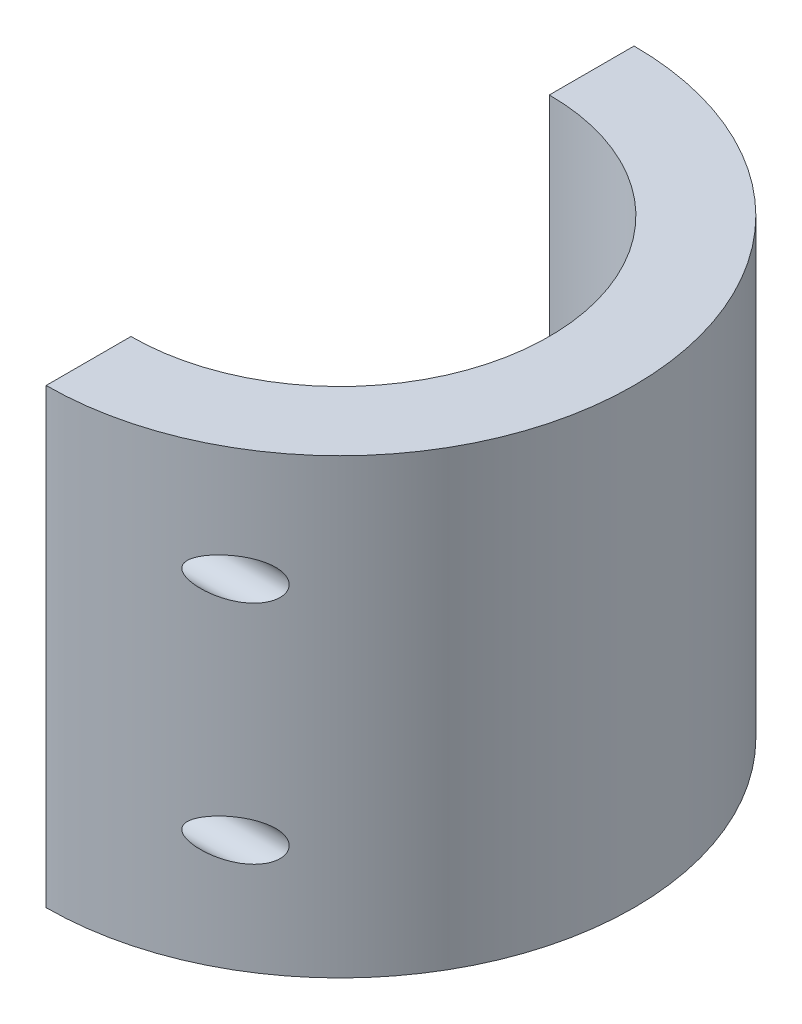
SolidWorks part; units mm, degrees
ref_plane "Front Plane" through (0, 0, 0) normal (0, 0, 1) x (1, 0, 0)
ref_plane "Top Plane" through (0, 0, 0) normal (0, 1, 0) x (1, 0, 0)
ref_plane "Right Plane" through (0, 0, 0) normal (1, 0, 0) x (0, 0, -1)
sketch "Sketch1" plane through (0, 0, 0) normal (0, 1, 0) x (1, 0, 0)
  line L0 (0, 13.208) -> (0, 9.398)
  line L1 (0, -9.398) -> (0, -13.208)
  arc A2 (0, -9.398) -> (0, 9.398) centre (0, 0) ccw
  arc A3 (0, -13.208) -> (0, 13.208) centre (0, 0) ccw
  dimension "D1" = 18.796
extrude "Boss-Extrude1" add sketch "Sketch1" along normal blind 20.32 contours L0 A2 L1 A3
sketch "Sketch3" plane through (0, 0, 0) normal (-1, 0, 0) x (0, 0, 1)
  line L0 (-11.303, 20.32) -> (-11.303, 15.24)
  line L1 (-13.208, 20.32) -> (-9.398, 20.32) construction
  line L2 (11.303, 20.32) -> (11.303, 15.24)
  line L3 (-11.303, 0) -> (-11.303, 5.08)
  line L4 (9.398, 0) -> (-9.398, 0) construction
  line L5 (9.398, 20.32) -> (13.208, 20.32) construction
  line L6 (11.303, 0) -> (11.303, 5.08)
  line L7 (13.208, 0) -> (-13.208, 0) construction
hole_wizard "Tap Drill for #2-56 Tap1" positions "3DSketch2" profile "Sketch4" hole size "#2-56" standard "ANSI Inch" end condition through all
sketch3d "3DSketch2"
  point P0 (0, 15.24, -11.303)
  point P3 (0, 15.24, 11.303)
  point P9 (0, 5.08, 11.303)
  point P15 (0, 5.08, -11.303)
sketch "Sketch4" plane through (0, 15.24, -11.303) normal (0, 1, 0) x (0, 0, 1)
  line L0 (0, 0) -> (0, 13.208)
  line L1 (0, 13.208) -> (0.889, 13.208)
  line L2 (0.889, 13.208) -> (0.889, 0)
  line L5 (0.889, 0) -> (0, 0)
  line L11 (0, -6.35) -> (0, 107.95) construction
  dimension "Thru Hole Dia." = 1.778
  dimension "Thru Hole Depth" = 13.208
